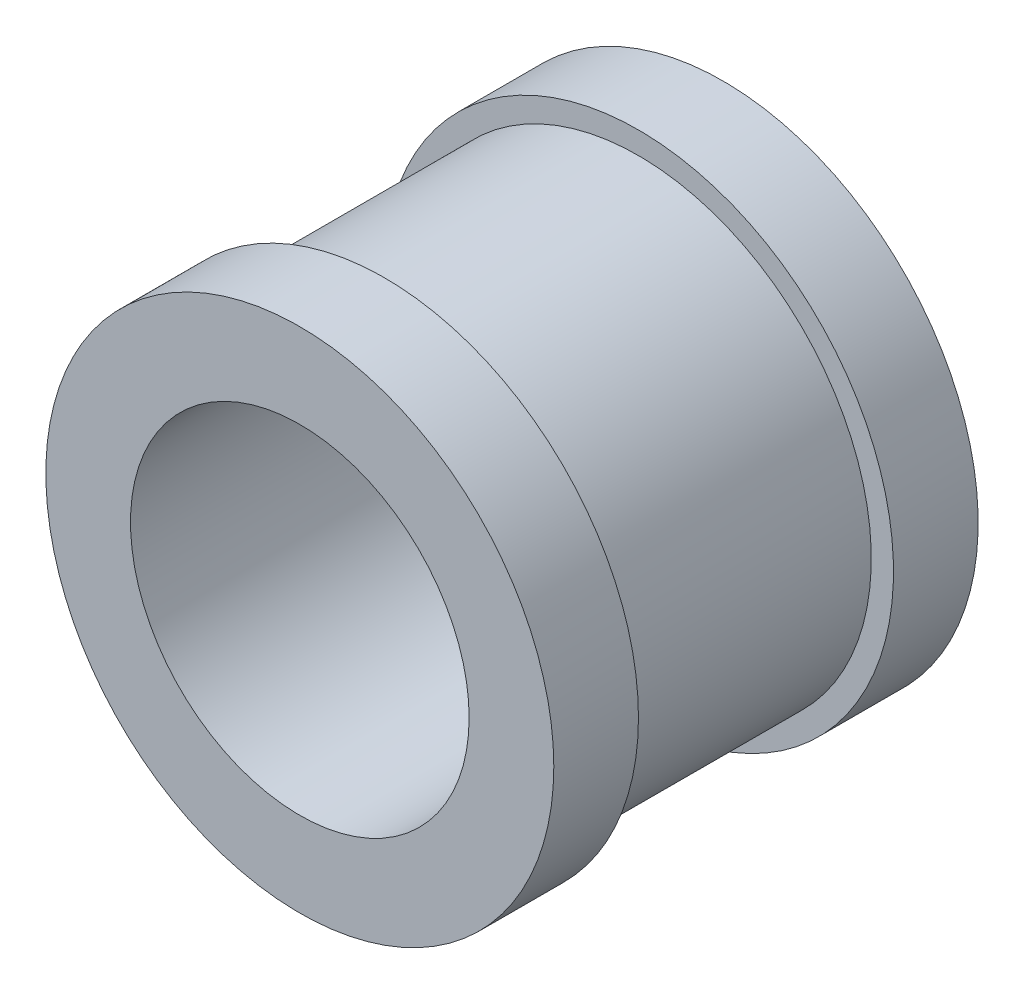
SolidWorks part; units mm, degrees
ref_plane "前视基准面" through (0, 0, 0) normal (0, 0, 1) x (1, 0, 0)
ref_plane "上视基准面" through (0, 0, 0) normal (0, 1, 0) x (1, 0, 0)
ref_plane "右视基准面" through (0, 0, 0) normal (1, 0, 0) x (0, 0, -1)
sketch "草图1" plane through (0, 0, 0) normal (0, 0, 1) x (1, 0, 0)
  circle A0 centre (0, 0) radius 2
  circle A1 centre (0, 0) radius 2.75
  dimension "D1" = 4
  dimension "D2" = 5.5
extrude "凸台-拉伸1" add sketch "草图1" along normal blind 5
sketch "草图2" plane through (0, 0, 5) normal (0, 0, 1) x (1, 0, 0)
  circle A0 centre (0, 0) radius 3
  circle A1 centre (0, 0) radius 2
  dimension "D1" = 6
extrude "凸台-拉伸2" add sketch "草图2" against normal blind 1
sketch "草图3" plane through (0, 0, 0) normal (0, 0, -1) x (-1, 0, 0)
  circle A0 centre (0, 0) radius 3.0124
  circle A1 centre (0, 0) radius 2
extrude "凸台-拉伸3" add sketch "草图3" against normal blind 1
